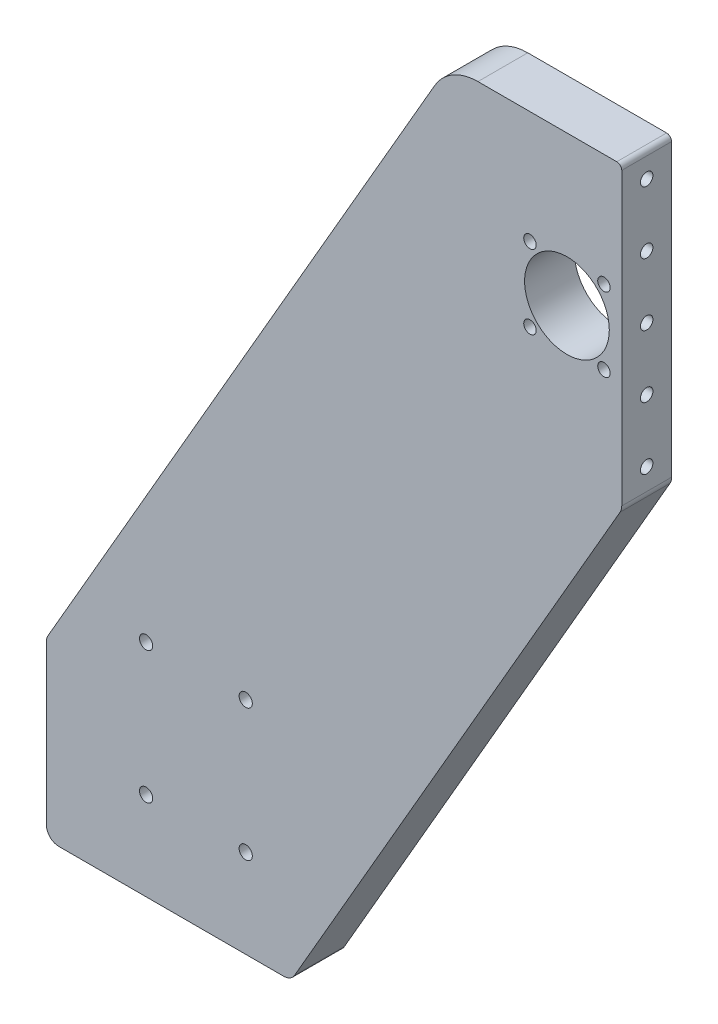
SolidWorks part; units mm, degrees
ref_plane "Piano frontale" through (0, 0, 0) normal (0, 0, 1) x (1, 0, 0)
ref_plane "Piano superiore" through (0, 0, 0) normal (0, 1, 0) x (1, 0, 0)
ref_plane "Piano destro" through (0, 0, 0) normal (1, 0, 0) x (0, 0, -1)
sketch "Schizzo1" plane through (0, 0, 0) normal (0, 0, 1) x (1, 0, 0)
  line L0 (5, 0) -> (95.2628, 0)
  line L1 (99.5929, 2.5) -> (230.2702, 228.8397)
  line L2 (230.9401, 231.3397) -> (230.9401, 348)
  line L3 (228.9401, 350) -> (173.2051, 350)
  line L4 (0, 68.6603) -> (0, 5)
  line L5 (155.8846, 340) -> (0.6699, 71.1603)
  line L9 (208.9401, 290) -> (194.0909, 304.8492) construction
  line L10 (208.9401, 290) -> (187.9401, 290) construction
  line L11 (208.9401, 290) -> (208.9401, 311) construction
  line L12 (50.1314, 0) -> (50.1314, 156.8301) construction
  circle A4 centre (208.9401, 290) radius 17
  circle A5 centre (208.9401, 290) radius 21 construction
  arc A6 (99.5929, 2.5) -> (95.2628, 0) centre (95.2628, 5) cw
  arc A7 (5, 0) -> (0, 5) centre (5, 5) cw
  arc A8 (0, 68.6603) -> (0.6699, 71.1603) centre (5, 68.6603) cw
  arc A9 (230.9401, 231.3397) -> (230.2702, 228.8397) centre (225.9401, 231.3397) cw
  arc A10 (230.9401, 348) -> (228.9401, 350) centre (228.9401, 348) ccw
  arc A11 (173.2051, 350) -> (155.8846, 340) centre (173.2051, 330) ccw
  circle A14 centre (223.7894, 304.8492) radius 2.5
  circle A15 centre (223.7894, 275.1508) radius 2.5
  circle A18 centre (194.0909, 275.1508) radius 2.5
  circle A19 centre (194.0909, 304.8492) radius 2.5
  point P27 (194.0909, 304.8492)
  point P28 (223.7894, 304.8492)
  point P29 (223.7894, 275.1508)
  point P30 (194.0909, 275.1508)
  point P31 (230.9401, 350)
  point P39 (0, 0)
  point P42 (0, 70)
  point P45 (230.9401, 230)
  point P48 (230.9401, 350)
  dimension "D6" = 60
  dimension "D9" = 34
  dimension "D11" = 45
  dimension "D14" = 5
  dimension "D15" = 5
  dimension "D17" = 42
  dimension "D12" = 2
  dimension "D1" = 120
  dimension "D2" = 120
  dimension "D3" = 70
  dimension "D4" = 350
  dimension "D5" = 120
  dimension "D10" = 22
extrude "Estrusione-Estrusione2" add sketch "Schizzo1" against normal blind 20
sketch "Sketch1" plane through (0, 0, 0) normal (0, -1, 0) x (1, 0, 0)
  line L0 (5, -10) -> (95.2628, -10) construction
  line L1 (5, -20) -> (5, 0) construction
  line L2 (95.2628, -20) -> (95.2628, 0) construction
  line L3 (50.1314, 0) -> (50.1314, -20) construction
  line L4 (5, 0) -> (95.2628, 0) construction
  line L5 (5, -20) -> (95.2628, -20) construction
  point P12 (50.1314, -10)
  point P13 (85.1314, -10)
  point P14 (15.1314, -10)
  dimension "D1" = 35
hole_wizard "M5 Tapped Hole1" positions "3DSketch1" profile "Sketch2" tap size "M5" standard "ISO"
sketch3d "3DSketch1"
  point P0 (50.1314, 0, -10)
  point P3 (85.1314, 0, -10)
  point P6 (15.1314, 0, -10)
sketch "Sketch2" plane through (50.1314, 0, -10) normal (1, 0, 0) x (0, 0, -1)
  line L0 (0, 0) -> (0, 18.6618)
  line L1 (0, 18.6618) -> (2.1, 17.4)
  line L2 (2.1, 17.4) -> (2.1, 0)
  line L5 (2.1, 0) -> (0, 0)
  line L10 (0, 18.6618) -> (-2.1, 17.4) construction
  line L11 (0, -6.35) -> (0, 107.95) construction
  dimension "Tap Drill Dia." = 4.2
  dimension "Tap Drill Depth" = 17.4
  dimension "Drill Angle" = 118
sketch "Sketch3" plane through (0, 0, -20) normal (0, 0, 1) x (1, 0, 0)
  line L0 (0, 68.6603) -> (0, 5) construction
  point P0 (40, 88.5)
  point P1 (80, 88.5)
  point P2 (80, 35.5)
  point P3 (40, 35.5)
  dimension "D1" = 40
  dimension "D2" = 53
  dimension "D3" = 40
hole_wizard "CBORE for M5 SHCS1" positions "3DSketch3" profile "Sketch5" counterbore size "M5" standard "ANSI Metric" end condition through all
sketch3d "3DSketch3"
  point P0 (80, 88.5, -20)
  point P3 (80, 35.5, -20)
  point P6 (40, 35.5, -20)
  point P9 (40, 88.5, -20)
sketch "Sketch5" plane through (80, 88.5, -20) normal (1, 0, 0) x (0, 1, 0)
  line L0 (0, 0) -> (0, 20)
  line L1 (0, 20) -> (2.65, 20)
  line L3 (2.65, 20) -> (2.65, 5)
  line L4 (5, 5) -> (2.65, 5)
  line L5 (5, 5) -> (5, 1.145)
  line L6 (5, 1.145) -> (6.145, 0)
  line L7 (6.145, 0) -> (0, 0)
  line L8 (-5, 1.145) -> (-6.145, 0) construction
  line L11 (0, -6.35) -> (0, 107.95) construction
  dimension "Thru Hole Dia." = 5.3
  dimension "Thru Hole Depth" = 20
  dimension "C'Bore Dia." = 10
  dimension "C'Bore Depth" = 5
  dimension "Near C'Sink Dia." = 12.29
  dimension "Near C'Sink Angle" = 90
sketch "Sketch6" plane through (230.9401, 0, 0) normal (1, 0, 0) x (0, 0, -1)
  point P0 (10, 340)
  point P1 (10, 315)
  point P2 (10, 290)
  point P3 (10, 265)
  point P4 (10, 240)
hole_wizard "M6 Tapped Hole1" positions "3DSketch4" profile "Sketch7" tap size "M6" standard "ISO"
sketch3d "3DSketch4"
  point P0 (230.9401, 340, -10)
  point P3 (230.9401, 315, -10)
  point P6 (230.9401, 290, -10)
  point P9 (230.9401, 265, -10)
  point P12 (230.9401, 240, -10)
sketch "Sketch7" plane through (230.9401, 340, -10) normal (0, 1, 0) x (0, 0, -1)
  line L0 (0, 0) -> (0, 20.5022)
  line L1 (0, 20.5022) -> (2.5, 19)
  line L2 (2.5, 19) -> (2.5, 0)
  line L5 (2.5, 0) -> (0, 0)
  line L10 (0, 20.5022) -> (-2.5, 19) construction
  line L11 (0, -6.35) -> (0, 107.95) construction
  dimension "Tap Drill Dia." = 5
  dimension "Tap Drill Depth" = 19
  dimension "Drill Angle" = 118
